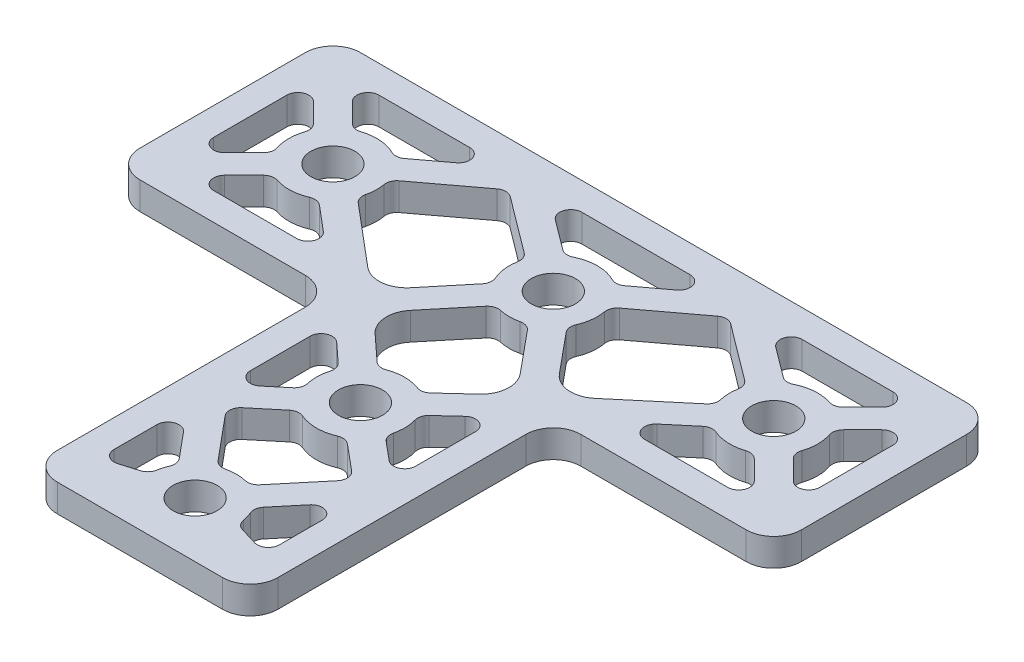
SolidWorks part; units mm, degrees
ref_plane "Front" through (0, 0, 0) normal (0, 0, 1) x (1, 0, 0)
ref_plane "Top" through (0, 0, 0) normal (0, 1, 0) x (1, 0, 0)
ref_plane "Right" through (0, 0, 0) normal (1, 0, 0) x (0, 0, -1)
sketch "Sketch1" plane through (0, 0, 0) normal (0, 1, 0) x (1, 0, 0)
  line L0 (0, 3.175) -> (0, 22.225)
  line L1 (3.175, 25.4) -> (73.025, 25.4)
  line L2 (76.2, 22.225) -> (76.2, 3.175)
  line L3 (73.025, 0) -> (53.975, 0)
  line L4 (50.8, -3.175) -> (50.8, -31.75)
  line L5 (47.625, -34.925) -> (28.575, -34.925)
  line L6 (25.4, -31.75) -> (25.4, -3.175)
  line L7 (22.225, 0) -> (3.175, 0)
  circle A0 centre (38.1, -9.525) radius 2.54
  circle A1 centre (38.1, -28.575) radius 2.54
  circle A2 centre (12.7, 12.7) radius 2.54
  circle A3 centre (38.1, 12.7) radius 2.54
  circle A4 centre (63.5, 12.7) radius 2.54
  arc A5 (0, 3.175) -> (3.175, 0) centre (3.175, 3.175) ccw
  arc A6 (0, 22.225) -> (3.175, 25.4) centre (3.175, 22.225) cw
  arc A7 (73.025, 25.4) -> (76.2, 22.225) centre (73.025, 22.225) cw
  arc A8 (76.2, 3.175) -> (73.025, 0) centre (73.025, 3.175) cw
  arc A9 (28.575, -34.925) -> (25.4, -31.75) centre (28.575, -31.75) cw
  arc A10 (50.8, -31.75) -> (47.625, -34.925) centre (47.625, -31.75) cw
  arc A11 (53.975, 0) -> (50.8, -3.175) centre (53.975, -3.175) ccw
  arc A12 (25.4, -3.175) -> (22.225, 0) centre (22.225, -3.175) ccw
  point P16 (38.1, -34.925)
  point P22 (0, 0)
  point P25 (0, 25.4)
  point P28 (76.2, 25.4)
  point P33 (25.4, -34.925)
  point P36 (50.8, -34.925)
  point P39 (50.8, 0)
  dimension "D6" = 9.525
  dimension "D10" = 5.08
  dimension "D12" = 3.175
  dimension "D1" = 25.4
  dimension "D2" = 76.2
  dimension "D3" = 25.4
  dimension "D4" = 25.4
  dimension "D5" = 34.925
  dimension "D7" = 19.05
  dimension "D8" = 12.7
  dimension "D9" = 12.7
  dimension "D11" = 3
extrude "Boss-Extrude1" add sketch "Sketch1" along normal blind 3.175
sketch "Sketch2" plane through (0, 3.175, 0) normal (0, 1, 0) x (1, 0, 0)
  line L8 (38.1, -28.8925) -> (47.625, -17.4625)
  line L9 (47.625, -17.4625) -> (38.1, -9.525)
  line L10 (12.7, 12.7) -> (25.4, 22.225)
  line L11 (25.4, 22.225) -> (38.1, 12.7)
  line L12 (12.7, 12.7) -> (38.1, 12.7) construction
  line L13 (12.7, 12.7) -> (27.6706, 0.0913)
  line L14 (27.6706, 0.0913) -> (38.1, 12.7)
  line L15 (27.6706, 0.0913) -> (38.1, -9.525)
  line L16 (3.175, 3.175) -> (22.225, 3.175)
  line L17 (28.575, -3.175) -> (28.575, -31.75)
  line L18 (28.575, -31.75) -> (47.625, -31.75)
  line L19 (47.625, -31.75) -> (47.625, -3.175)
  line L20 (53.975, 3.175) -> (73.025, 3.175)
  line L21 (73.025, 3.175) -> (73.025, 22.225)
  line L22 (73.025, 22.225) -> (3.175, 22.225)
  line L23 (3.175, 22.225) -> (3.175, 3.175)
  line L24 (3.175, 3.175) -> (22.225, 3.175)
  line L25 (28.575, -3.175) -> (28.575, -31.75)
  line L27 (47.625, -31.75) -> (47.625, -3.175)
  line L28 (53.975, 3.175) -> (73.025, 3.175)
  line L29 (73.025, 3.175) -> (73.025, 22.225)
  line L30 (73.025, 22.225) -> (3.175, 22.225)
  line L31 (3.175, 22.225) -> (3.175, 3.175)
  line L32 (38.1, -9.525) -> (28.575, -17.4625)
  line L33 (28.575, -17.4625) -> (38.1, -28.8925)
  line L34 (28.575, -31.75) -> (38.1, -28.8925)
  line L35 (47.625, -31.75) -> (38.1, -28.8925)
  line L36 (38.1, 22.225) -> (38.1, 31.9917) construction
  line L37 (48.5294, 0.0913) -> (38.1, -9.525)
  line L38 (48.5294, 0.0913) -> (38.1, 12.7)
  line L39 (63.5, 12.7) -> (48.5294, 0.0913)
  line L40 (63.5, 12.7) -> (50.8, 22.225)
  line L41 (50.8, 22.225) -> (38.1, 12.7)
  line L42 (12.7, 12.7) -> (3.175, 22.225)
  line L43 (3.175, 3.175) -> (12.7, 12.7)
  line L44 (73.025, 3.175) -> (63.5, 12.7)
  line L45 (63.5, 12.7) -> (73.025, 22.225)
  line L46 (2.0525, 4.2975) -> (11.5775, 13.8225)
  line L47 (11.5775, 11.5775) -> (2.0525, 21.1025)
  line L48 (11.7475, 13.97) -> (25.4, 24.2094)
  line L49 (25.4, 24.2094) -> (39.0525, 13.97)
  line L50 (13.7227, 13.9142) -> (28.6932, 1.3055)
  line L51 (26.4473, 1.1031) -> (36.8767, 13.7118)
  line L52 (62.5475, 11.43) -> (50.8, 20.2406)
  line L53 (50.8, 20.2406) -> (39.0525, 11.43)
  line L54 (47.3062, -0.9206) -> (36.8767, 11.6882)
  line L55 (64.5227, 11.4858) -> (49.5521, -1.123)
  line L56 (62.3775, 13.8225) -> (71.9025, 23.3475)
  line L57 (71.9025, 2.0525) -> (62.3775, 11.5775)
  line L58 (49.6056, -1.0759) -> (39.1761, -10.6921)
  line L59 (28.7467, 1.2584) -> (39.1761, -8.3579)
  line L60 (39.1163, -10.7446) -> (30.8108, -17.6658)
  line L61 (30.8108, -17.6658) -> (39.3196, -27.8762)
  line L62 (28.1188, -30.2295) -> (37.6438, -27.372)
  line L63 (47.1688, -33.2705) -> (37.6438, -30.413)
  line L64 (36.8804, -27.8762) -> (45.3892, -17.6658)
  line L65 (45.3892, -17.6658) -> (37.0837, -10.7446)
  line L66 (4.2975, 2.0525) -> (13.8225, 11.5775)
  line L67 (13.8225, 13.8225) -> (4.2975, 23.3475)
  line L68 (13.6525, 11.43) -> (25.4, 20.2406)
  line L69 (25.4, 20.2406) -> (37.1475, 11.43)
  line L70 (11.6773, 11.4858) -> (26.6479, -1.123)
  line L71 (28.8938, -0.9206) -> (39.3233, 11.6882)
  line L72 (64.4525, 13.97) -> (50.8, 24.2094)
  line L73 (50.8, 24.2094) -> (37.1475, 13.97)
  line L74 (49.7527, 1.1031) -> (39.3233, 13.7118)
  line L75 (62.4773, 13.9142) -> (47.5068, 1.3055)
  line L76 (64.6225, 11.5775) -> (74.1475, 21.1025)
  line L77 (74.1475, 4.2975) -> (64.6225, 13.8225)
  line L78 (47.4533, 1.2584) -> (37.0239, -8.3579)
  line L79 (26.5944, -1.0759) -> (37.0239, -10.6921)
  line L80 (37.0837, -8.3054) -> (26.3392, -17.2592)
  line L81 (26.3392, -17.2592) -> (36.8804, -29.9088)
  line L82 (29.0312, -33.2705) -> (38.5562, -30.413)
  line L83 (48.0812, -30.2295) -> (38.5562, -27.372)
  line L84 (39.3196, -29.9088) -> (49.8608, -17.2592)
  line L85 (49.8608, -17.2592) -> (39.1163, -8.3054)
  line L86 (31.4538, -32.5438) -> (44.7462, -32.5438)
  line L87 (28.575, -34.925) -> (47.625, -34.925) construction
  circle A8 centre (12.7, 12.7) radius 5.08
  circle A9 centre (38.1, 12.7) radius 5.08
  circle A10 centre (63.5, 12.7) radius 5.08
  circle A11 centre (38.1, -9.525) radius 5.08
  circle A12 centre (38.1, -28.8925) radius 5.08
  arc A16 (28.575, -3.175) -> (22.225, 3.175) centre (22.225, -3.175) ccw
  arc A17 (53.975, 3.175) -> (47.625, -3.175) centre (53.975, -3.175) ccw
  arc A18 (28.575, -3.175) -> (22.225, 3.175) centre (22.225, -3.175) ccw
  arc A19 (53.975, 3.175) -> (47.625, -3.175) centre (53.975, -3.175) ccw
  point P15 (25.4, 12.7)
  dimension "D2" = 10.16
  dimension "D5" = 2.3813
  dimension "D1" = 3.175
  dimension "D3" = 1.5875
  dimension "D4" = 1.5875
extrude "Cut-Extrude1" cut sketch "Sketch2" against normal through all contours A12 L81 L25 L62 | A12 L83 L27 L84 | A12 L64 L65 A11 L60 L61 | A18 L25 L80 A11 L79 | A19 L58 A11 L85 L27 | A11 L78 L54 A9 L71 L59 | A9 L69 L68 A8 L50 L51 | A8 L48 L30 L67 | A8 L47 L31 L46 | A8 L66 L24 L70 | A10 L52 L53 A9 L74 L75 | A9 L73 L30 L49 | A10 L56 L30 L72 | A10 L55 L28 L57 | A10 L77 L29 L76
fillet "Fillet1" radius 1.27 64 edges at (35.192, 1.5875, -16.8653) (28.0458, 1.5875, -22.225) (48.1542, 1.5875, -22.225) (41.008, 1.5875, -16.8653) (68.0347, 1.5875, -14.9897) (73.025, 1.5875, -19.9799) (73.025, 1.5875, -5.4201) (68.0347, 1.5875, -10.4103) (33.801, 1.5875, -9.9934) (17.4136, 1.5875, -10.8056) (17.513, 1.5875, -14.3253) (25.4, 1.5875, -20.2406) (33.287, 1.5875, -14.3253) (15.3682, 1.5875, -8.3772) (21.5449, 1.5875, -3.175) (5.4201, 1.5875, -3.175) (10.4103, 1.5875, -8.1653) (42.4088, 1.5875, 26.2017) (47.625, 1.5875, 19.9423) (47.625, 1.5875, 30.0926) (43.1782, 1.5875, 28.7586) (47.625, 1.5875, 15.396) (42.8234, 1.5875, 11.3947) (42.7238, 1.5875, 7.421) (47.6311, 1.5875, 2.8963) (28.5689, 1.5875, 2.8963) (33.4762, 1.5875, 7.421) (33.3766, 1.5875, 11.3947) (28.575, 1.5875, 15.396) (8.1653, 1.5875, -10.4103) (3.175, 1.5875, -5.4201) (8.1653, 1.5875, -14.9897) (36.2303, 1.5875, 24.1691) (30.8108, 1.5875, 17.6658) (35.4092, 1.5875, 13.8338) (40.7908, 1.5875, 13.8338) (45.3892, 1.5875, 17.6658) (39.9697, 1.5875, 24.1691) (65.7897, 1.5875, -8.1653) (70.7799, 1.5875, -3.175) (54.6551, 1.5875, -3.175) (60.8318, 1.5875, -8.3772) (33.0218, 1.5875, 28.7586) (28.575, 1.5875, 30.0926) (28.575, 1.5875, 19.9423) (33.7912, 1.5875, 26.2017) (35.6284, 1.5875, 5.0868) (36.2476, 1.5875, -7.9698) (39.9524, 1.5875, -7.9698) (40.5716, 1.5875, 5.0868) (10.4103, 1.5875, -17.2347) (5.4201, 1.5875, -22.225) (22.7542, 1.5875, -22.225) (15.608, 1.5875, -16.8653) (60.592, 1.5875, -16.8653) (53.4458, 1.5875, -22.225) (70.7799, 1.5875, -22.225) (65.7897, 1.5875, -17.2347) (58.7864, 1.5875, -10.8056) (42.399, 1.5875, -9.9934) (42.913, 1.5875, -14.3253) (50.8, 1.5875, -20.2406) (58.687, 1.5875, -14.3253) (3.175, 1.5875, -19.9799)
fillet "Fillet2" radius 3.175 4 edges at (48.7318, 1.5875, -2.3373) (27.4682, 1.5875, -2.3373) (29.8526, 1.5875, -0.2386) (46.3474, 1.5875, -0.2386)
